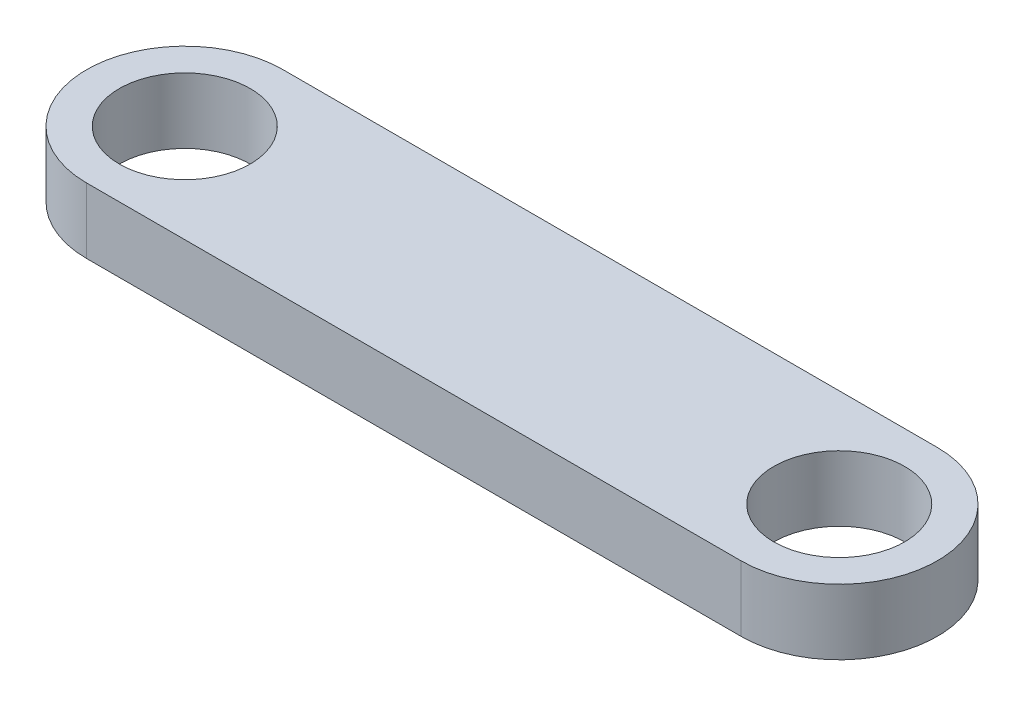
SolidWorks part; units mm, degrees
ref_plane "Front" through (0, 0, 0) normal (0, 0, 1) x (1, 0, 0)
ref_plane "Top" through (0, 0, 0) normal (0, 1, 0) x (1, 0, 0)
ref_plane "Right" through (0, 0, 0) normal (1, 0, 0) x (0, 0, -1)
sketch "Sketch1" plane through (0, 0, 0) normal (0, 1, 0) x (1, 0, 0)
  line L0 (0, 0) -> (-63.5, 0) construction
  line L1 (0, -9.525) -> (-63.5, -9.525)
  line L2 (0, 9.525) -> (-63.5, 9.525)
  arc A0 (0, -9.525) -> (0, 9.525) centre (0, 0) ccw
  arc A1 (-63.5, 9.525) -> (-63.5, -9.525) centre (-63.5, 0) ccw
  circle A2 centre (-63.5, 0) radius 6.35
  circle A3 centre (0, 0) radius 6.35
  point P3 (-31.75, 0)
  dimension "D1" = 9.525
  dimension "D3" = 12.7
  dimension "D2" = 63.5
extrude "Boss-Extrude1" add sketch "Sketch1" along normal blind 6.35
